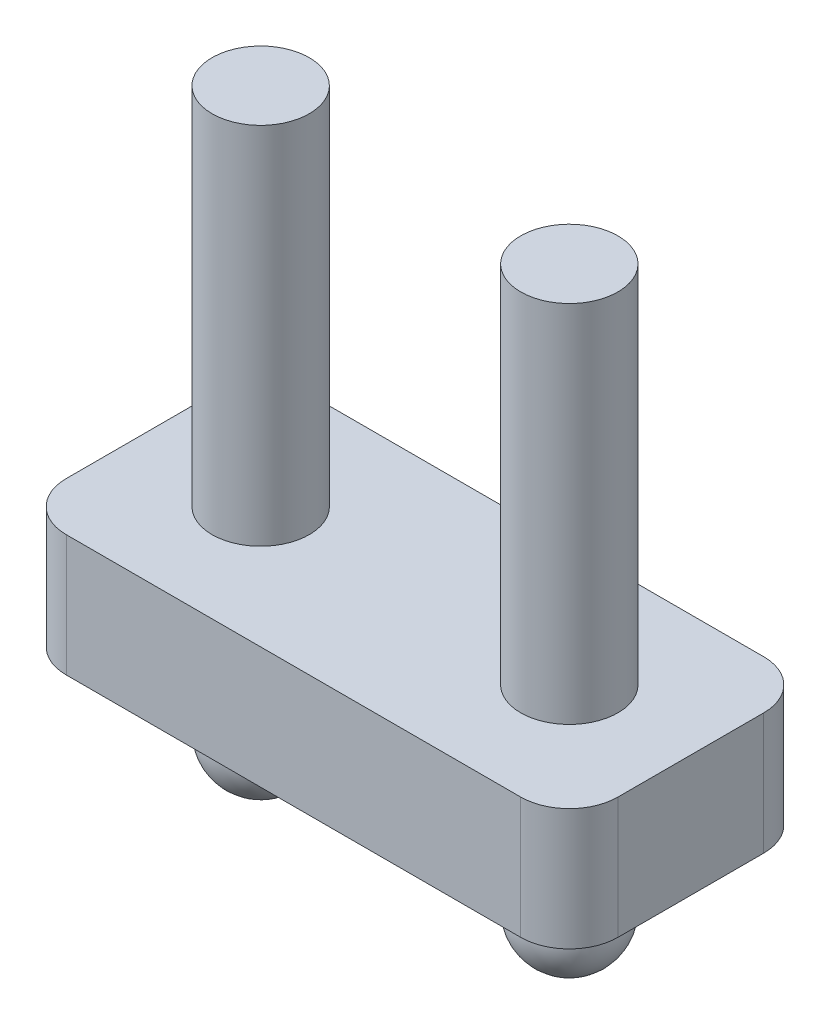
SolidWorks part; units mm, degrees
ref_plane "Front Plane" through (0, 0, 0) normal (0, 0, 1) x (1, 0, 0)
ref_plane "Top Plane" through (0, 0, 0) normal (0, 1, 0) x (1, 0, 0)
ref_plane "Right Plane" through (0, 0, 0) normal (1, 0, 0) x (0, 0, -1)
sketch "Sketch1" plane through (0, 0, 0) normal (0, 1, 0) x (1, 0, 0)
  line L1 (0, 0) -> (4.54, 0)
  line L2 (0, 0) -> (0, 2)
  line L3 (0, 2) -> (4.54, 2)
  line L4 (4.54, 0) -> (4.54, 2)
  circle A0 centre (1, 1) radius 0.4
  circle A1 centre (3.54, 1) radius 0.4
  dimension "D1" = 0.8
  dimension "D2" = 0.8
  dimension "D5" = 1
  dimension "D6" = 1
  dimension "D8" = 1
  dimension "D3" = 2.54
  dimension "D4" = 1
  dimension "D7" = 2
extrude "Boss-Extrude1" add sketch "Sketch1" along normal blind 1
fillet "Fillet2" radius 0.4 4 edges at (0, 0.5, -2) (4.54, 0.5, -2) (4.54, 0.5, 0) (0, 0.5, 0)
sketch "Sketch2" plane through (0, 1, 0) normal (0, 1, 0) x (1, 0, 0)
  circle A0 centre (1, 1) radius 0.4
  circle A1 centre (3.54, 1) radius 0.4
extrude "Boss-Extrude2" add sketch "Sketch2" along normal blind 3 and the other way blind 2
fillet "Fillet1" radius 0.4 2 edges at (1, -1, -0.6) (3.54, -1, -0.6)
